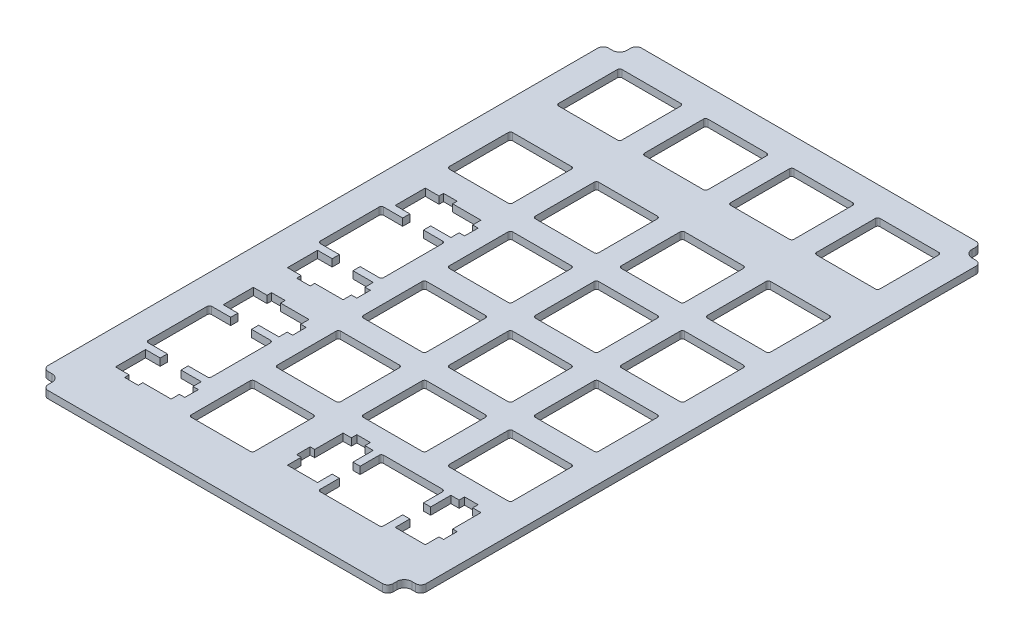
SolidWorks part; units mm, degrees
ref_plane "前视基准面" through (0, 0, 0) normal (0, 0, 1) x (1, 0, 0)
ref_plane "上视基准面" through (0, 0, 0) normal (0, 1, 0) x (1, 0, 0)
ref_plane "右视基准面" through (0, 0, 0) normal (1, 0, 0) x (0, 0, -1)
sketch "草图1" plane through (0, 0, 0) normal (0, 1, 0) x (1, 0, 0)
  line L17 (-11.3508, 119.1658) -> (-10.5008, 119.1658)
  line L18 (-8.8508, 120.8158) -> (-8.8508, 121.6658)
  line L19 (50.8492, 119.1658) -> (49.9992, 119.1658)
  line L20 (48.3492, 120.8158) -> (48.3492, 121.6658)
  line L21 (47.1992, 122.8158) -> (-7.7008, 122.8158)
  line L22 (-8.8508, 121.6658) -> (-8.8508, 120.8158)
  line L23 (-10.5008, 119.1658) -> (-11.3508, 119.1658)
  line L24 (-12.5008, 118.0158) -> (-12.5008, -3.4717)
  line L25 (-11.3508, -4.6217) -> (-10.5008, -4.6217)
  line L26 (-8.8508, -6.2717) -> (-8.8508, -7.1217)
  line L27 (-7.7008, -8.2717) -> (47.1992, -8.2717)
  line L28 (48.3492, -7.1217) -> (48.3492, -6.2717)
  line L29 (49.9992, -4.6217) -> (50.8492, -4.6217)
  line L30 (51.9992, -3.4717) -> (51.9992, 97.2055)
  line L37 (-11.3508, -4.6217) -> (-10.5008, -4.6217)
  line L38 (-8.8508, -6.2717) -> (-8.8508, -7.1217)
  line L43 (68.9992, 119.1658) -> (69.8492, 119.1658)
  line L44 (67.3492, 121.6658) -> (67.3492, 120.8158)
  line L45 (66.1992, 122.8158) -> (-7.7008, 122.8158)
  line L46 (70.9992, -3.4717) -> (70.9992, 118.0158)
  line L49 (66.1992, -8.2717) -> (-7.7008, -8.2717)
  line L50 (-12.5008, 118.0158) -> (-12.5008, -3.4717)
  line L53 (69.8492, -4.6217) -> (68.9992, -4.6217)
  line L54 (67.3492, -6.2717) -> (67.3492, -7.1217)
  line L266 (50.9992, 117.4055) -> (51.9992, 117.4055)
  line L268 (51.9992, 117.4055) -> (51.9992, 118.0158)
  line L270 (51.9992, 97.2055) -> (50.9992, 97.2055)
  line L272 (50.9992, 97.2055) -> (50.9992, 117.4055)
  arc A9 (-11.3508, 119.1658) -> (-12.5008, 118.0158) centre (-11.3508, 118.0158) ccw
  arc A10 (-10.5008, 119.1658) -> (-8.8508, 120.8158) centre (-10.5008, 120.8158) ccw
  arc A11 (-7.7008, 122.8158) -> (-8.8508, 121.6658) centre (-7.7008, 121.6658) ccw
  arc A12 (70.9992, 118.0158) -> (69.8492, 119.1658) centre (69.8492, 118.0158) ccw
  arc A13 (67.3492, 120.8158) -> (68.9992, 119.1658) centre (68.9992, 120.8158) ccw
  arc A14 (51.9992, 118.0158) -> (50.8492, 119.1658) centre (50.8492, 118.0158) ccw
  arc A15 (48.3492, 120.8158) -> (49.9992, 119.1658) centre (49.9992, 120.8158) ccw
  arc A16 (48.3492, 121.6658) -> (47.1992, 122.8158) centre (47.1992, 121.6658) ccw
  arc A17 (-7.7008, 122.8158) -> (-8.8508, 121.6658) centre (-7.7008, 121.6658) ccw
  arc A18 (-10.5008, 119.1658) -> (-8.8508, 120.8158) centre (-10.5008, 120.8158) ccw
  arc A19 (-11.3508, 119.1658) -> (-12.5008, 118.0158) centre (-11.3508, 118.0158) ccw
  arc A20 (-12.5008, -3.4717) -> (-11.3508, -4.6217) centre (-11.3508, -3.4717) ccw
  arc A21 (-8.8508, -6.2717) -> (-10.5008, -4.6217) centre (-10.5008, -6.2717) ccw
  arc A22 (-8.8508, -7.1217) -> (-7.7008, -8.2717) centre (-7.7008, -7.1217) ccw
  arc A23 (47.1992, -8.2717) -> (48.3492, -7.1217) centre (47.1992, -7.1217) ccw
  arc A24 (49.9992, -4.6217) -> (48.3492, -6.2717) centre (49.9992, -6.2717) ccw
  arc A25 (50.8492, -4.6217) -> (51.9992, -3.4717) centre (50.8492, -3.4717) ccw
  arc A32 (-12.5008, -3.4717) -> (-11.3508, -4.6217) centre (-11.3508, -3.4717) ccw
  arc A33 (-8.8508, -6.2717) -> (-10.5008, -4.6217) centre (-10.5008, -6.2717) ccw
  arc A34 (-8.8508, -7.1217) -> (-7.7008, -8.2717) centre (-7.7008, -7.1217) ccw
  arc A38 (67.3492, 121.6658) -> (66.1992, 122.8158) centre (66.1992, 121.6658) ccw
  arc A45 (69.8492, -4.6217) -> (70.9992, -3.4717) centre (69.8492, -3.4717) ccw
  arc A46 (68.9992, -4.6217) -> (67.3492, -6.2717) centre (68.9992, -6.2717) ccw
  arc A47 (66.1992, -8.2717) -> (67.3492, -7.1217) centre (66.1992, -7.1217) ccw
  dimension "D1" = 0
extrude "凸台-拉伸1" add sketch "草图1" along normal blind 1.6
sketch "草图6" plane through (0, 0, 0) normal (0, -1, 0) x (1, 0, 0)
  line L0 (-20.4509, -109.5658) -> (75.1048, -109.5658) construction
  line L1 (-30.8327, -47.4158) -> (78.7033, -47.4158) construction
  line L2 (29.2492, 25.694) -> (29.2492, -129.0357) construction
  line L3 (51.2492, -2.4158) -> (64.2492, -2.4158)
  line L4 (64.7492, -2.9158) -> (64.7492, -15.9158)
  line L5 (64.2492, -16.4158) -> (51.2492, -16.4158)
  line L6 (50.7492, -2.9158) -> (50.7492, -15.9158)
  line L7 (-28.6594, -9.4158) -> (85.6489, -9.4158) construction
  line L10 (67.2492, -99.3158) -> (-8.7508, -99.3158) construction
  line L11 (-9.5008, -100.0658) -> (-9.5008, -105.0658) construction
  line L12 (67.9992, -95.0158) -> (67.9992, 0.1842) construction
  line L13 (67.2492, 0.9342) -> (-8.7508, 0.9342) construction
  line L14 (67.9992, -105.0658) -> (67.9992, -100.0658) construction
  line L15 (67.9992, -119.0658) -> (67.9992, -114.0658) construction
  line L16 (-8.7508, -119.8158) -> (67.2492, -119.8158) construction
  line L17 (-9.5008, -114.0658) -> (-9.5008, -119.0658) construction
  line L18 (-9.5008, 0.1842) -> (-9.5008, -95.0158) construction
  line L19 (-8.7508, -95.7658) -> (67.2492, -95.7658) construction
  arc A0 (50.7492, -15.9158) -> (51.2492, -16.4158) centre (51.2492, -15.9158) ccw
  arc A1 (64.2492, -16.4158) -> (64.7492, -15.9158) centre (64.2492, -15.9158) ccw
  arc A2 (51.2492, -2.4158) -> (50.7492, -2.9158) centre (51.2492, -2.9158) ccw
  arc A3 (64.2492, -2.4158) -> (64.7492, -2.9158) centre (64.2492, -2.9158) cw
  dimension "D2" = 0.5
  dimension "D1" = 14
  dimension "D3" = 21.5
  dimension "D4" = 31
extrude "切除-拉伸3" cut sketch "草图6" against normal up to next
pattern_linear "阵列(线性)1" count 5 spacing 19 along (0, 0, -1) count 4 spacing 19 along (-1, 0, 0) skipping (0, 3), (1, 3), (2, 3), (3, 3) of "切除-拉伸3"
pattern_linear "阵列(线性)2" count 2 spacing 100.15 along (0, 0, -1) count 4 spacing 19 along (-1, 0, 0) skipping (0, 1), (0, 2), (0, 3) of "切除-拉伸3"
sketch "草图3" plane through (0, 1.6, 0) normal (0, 1, 0) x (1, 0, 0)
  line L0 (-24.3873, 18.9158) -> (58.3219, 18.9158) construction
  line L1 (0.7492, -13.1729) -> (0.7492, 58.2769) construction
  line L2 (-6.2508, 12.4158) -> (-6.2508, 25.4158)
  line L3 (7.7492, 25.4158) -> (7.7492, 12.4158)
  line L4 (-5.7508, 25.9158) -> (-1.5508, 25.9158)
  line L9 (-6.2508, 25.9158) -> (7.7492, 11.9158) construction
  line L10 (-6.2508, 11.9158) -> (7.7492, 25.9158) construction
  line L11 (-1.5508, 25.9158) -> (-1.5508, 27.4958)
  line L12 (-4.7808, 27.4958) -> (-1.5508, 27.4958)
  line L13 (-4.7808, 27.4958) -> (-4.7808, 34.1458)
  line L14 (-4.7808, 34.1458) -> (-1.7508, 34.1458)
  line L15 (-1.7508, 34.1458) -> (-1.7508, 35.1458)
  line L16 (-1.7508, 35.1458) -> (1.2492, 35.1458)
  line L17 (1.2492, 35.1458) -> (1.2492, 34.1458)
  line L18 (1.2492, 34.1458) -> (7.5192, 34.1458)
  line L19 (7.5192, 34.1458) -> (7.5192, 32.3208)
  line L20 (7.5192, 32.3208) -> (8.7192, 32.3208)
  line L21 (8.7192, 32.3208) -> (8.7192, 29.3208)
  line L22 (8.7192, 29.3208) -> (7.5192, 29.3208)
  line L23 (7.5192, 29.3208) -> (7.5192, 27.4958)
  line L24 (7.5192, 27.4958) -> (3.0492, 27.4958)
  line L25 (3.0492, 27.4958) -> (3.0492, 25.9158)
  line L26 (3.0492, 25.9158) -> (7.2492, 25.9158)
  line L27 (3.0492, 11.9158) -> (7.2492, 11.9158)
  line L28 (3.0492, 10.3358) -> (3.0492, 11.9158)
  line L29 (7.5192, 10.3358) -> (3.0492, 10.3358)
  line L30 (7.5192, 8.5108) -> (7.5192, 10.3358)
  line L31 (8.7192, 8.5108) -> (7.5192, 8.5108)
  line L32 (8.7192, 5.5108) -> (8.7192, 8.5108)
  line L33 (7.5192, 5.5108) -> (8.7192, 5.5108)
  line L34 (7.5192, 3.6858) -> (7.5192, 5.5108)
  line L35 (1.2492, 3.6858) -> (7.5192, 3.6858)
  line L36 (1.2492, 2.6858) -> (1.2492, 3.6858)
  line L37 (-1.7508, 2.6858) -> (1.2492, 2.6858)
  line L38 (-1.7508, 3.6858) -> (-1.7508, 2.6858)
  line L39 (-4.7808, 3.6858) -> (-1.7508, 3.6858)
  line L40 (-4.7808, 10.3358) -> (-4.7808, 3.6858)
  line L41 (-4.7808, 10.3358) -> (-1.5508, 10.3358)
  line L42 (-1.5508, 11.9158) -> (-1.5508, 10.3358)
  line L43 (-5.7508, 11.9158) -> (-1.5508, 11.9158)
  line L46 (-6.2508, 50.4158) -> (-6.2508, 63.4158)
  line L47 (7.7492, 63.4158) -> (7.7492, 50.4158)
  line L48 (-5.7508, 63.9158) -> (-1.5508, 63.9158)
  line L49 (-1.5508, 63.9158) -> (-1.5508, 65.4958)
  line L50 (-4.7808, 65.4958) -> (-1.5508, 65.4958)
  line L51 (-4.7808, 65.4958) -> (-4.7808, 72.1458)
  line L52 (-4.7808, 72.1458) -> (-1.7508, 72.1458)
  line L53 (-1.7508, 72.1458) -> (-1.7508, 73.1458)
  line L54 (-1.7508, 73.1458) -> (1.2492, 73.1458)
  line L55 (1.2492, 73.1458) -> (1.2492, 72.1458)
  line L56 (1.2492, 72.1458) -> (7.5192, 72.1458)
  line L57 (7.5192, 72.1458) -> (7.5192, 70.3208)
  line L58 (7.5192, 70.3208) -> (8.7192, 70.3208)
  line L59 (8.7192, 70.3208) -> (8.7192, 67.3208)
  line L60 (8.7192, 67.3208) -> (7.5192, 67.3208)
  line L61 (7.5192, 67.3208) -> (7.5192, 65.4958)
  line L62 (7.5192, 65.4958) -> (3.0492, 65.4958)
  line L63 (3.0492, 65.4958) -> (3.0492, 63.9158)
  line L64 (3.0492, 63.9158) -> (7.2492, 63.9158)
  line L65 (3.0492, 49.9158) -> (7.2492, 49.9158)
  line L66 (3.0492, 48.3358) -> (3.0492, 49.9158)
  line L67 (7.5192, 48.3358) -> (3.0492, 48.3358)
  line L68 (7.5192, 46.5108) -> (7.5192, 48.3358)
  line L69 (8.7192, 46.5108) -> (7.5192, 46.5108)
  line L70 (8.7192, 43.5108) -> (8.7192, 46.5108)
  line L71 (7.5192, 43.5108) -> (8.7192, 43.5108)
  line L72 (7.5192, 41.6858) -> (7.5192, 43.5108)
  line L73 (1.2492, 41.6858) -> (7.5192, 41.6858)
  line L74 (1.2492, 40.6858) -> (1.2492, 41.6858)
  line L75 (-1.7508, 40.6858) -> (1.2492, 40.6858)
  line L76 (-1.7508, 41.6858) -> (-1.7508, 40.6858)
  line L77 (-4.7808, 41.6858) -> (-1.7508, 41.6858)
  line L78 (-4.7808, 48.3358) -> (-4.7808, 41.6858)
  line L79 (-4.7808, 48.3358) -> (-1.5508, 48.3358)
  line L80 (-1.5508, 49.9158) -> (-1.5508, 48.3358)
  line L81 (-5.7508, 49.9158) -> (-1.5508, 49.9158)
  line L82 (-6.2508, 63.9158) -> (7.7492, 49.9158) construction
  line L83 (-6.2508, 49.9158) -> (7.7492, 63.9158) construction
  line L84 (32.2492, 16.4158) -> (45.2492, 16.4158) construction
  arc A0 (-6.2508, 25.4158) -> (-5.7508, 25.9158) centre (-5.7508, 25.4158) cw
  arc A1 (7.2492, 25.9158) -> (7.7492, 25.4158) centre (7.2492, 25.4158) cw
  arc A2 (7.2492, 11.9158) -> (7.7492, 12.4158) centre (7.2492, 12.4158) ccw
  arc A3 (-6.2508, 12.4158) -> (-5.7508, 11.9158) centre (-5.7508, 12.4158) ccw
  arc A4 (-6.2508, 63.4158) -> (-5.7508, 63.9158) centre (-5.7508, 63.4158) cw
  arc A5 (7.2492, 63.9158) -> (7.7492, 63.4158) centre (7.2492, 63.4158) cw
  arc A6 (7.2492, 49.9158) -> (7.7492, 50.4158) centre (7.2492, 50.4158) ccw
  arc A7 (-6.2508, 50.4158) -> (-5.7508, 49.9158) centre (-5.7508, 50.4158) ccw
  point P4 (0.7492, 18.9158)
  point P5 (0.7492, 18.9158)
  point P17 (-3.6508, 25.9158)
  point P64 (0.7492, 56.9158)
  point P65 (0.7492, 56.9158)
  dimension "D1" = 14
  dimension "D2" = 4.2
  dimension "D3" = 1.58
  dimension "D4" = 3.23
  dimension "D5" = 6.65
  dimension "D6" = 3.03
  dimension "D7" = 3
  dimension "D8" = 1
  dimension "D9" = 6.27
  dimension "D10" = 3
  dimension "D11" = 1.2
  dimension "D12" = 0.5
  dimension "D13" = 13
  dimension "D14" = 45
  dimension "D15" = 4.47
  dimension "D16" = 2
  dimension "D17" = 2.5
  dimension "D18" = 38
extrude "切除-拉伸2" cut sketch "草图3" against normal up to surface (1.6 mm away) up to face at (57.7492, 0, -109.5658)
sketch "草图7" plane through (0, 1.6, 0) normal (0, 1, 0) x (1, 0, 0)
  line L1 (30.8591, 16.9848) -> (66.3802, 16.9848)
  line L2 (30.8591, 16.9848) -> (30.8591, 1.1193)
  line L3 (30.8591, 1.1193) -> (66.3802, 1.1193)
  line L4 (66.3802, 16.9848) -> (66.3802, 1.1193)
extrude "凸台-拉伸2" add sketch "草图7" against normal up to surface (1.6 mm away) up to face at (2.1472, 0, -18.9158)
sketch "草图8" plane through (0, 1.6, 0) normal (0, 1, 0) x (1, 0, 0)
  line L0 (26.7492, 9.4158) -> (76.4498, 9.4158) construction
  line L1 (26.7492, 15.9158) -> (26.7492, 2.9158) construction
  line L2 (48.2492, 23.7044) -> (48.2492, -8.9571) construction
  line L3 (48.2492, 2.4158) -> (48.2492, 16.4158) construction
  line L4 (48.2492, 9.4158) -> (41.7492, 9.4158) construction
  line L72 (58.6542, 16.1858) -> (56.8292, 16.1858)
  line L73 (58.6542, 17.3858) -> (58.6542, 16.1858)
  line L74 (61.6542, 17.3858) -> (58.6542, 17.3858)
  line L75 (61.6542, 16.1858) -> (61.6542, 17.3858)
  line L76 (63.4792, 16.1858) -> (61.6542, 16.1858)
  line L77 (63.4792, 9.9158) -> (63.4792, 16.1858)
  line L78 (64.4792, 9.9158) -> (63.4792, 9.9158)
  line L79 (64.4792, 6.9158) -> (64.4792, 9.9158)
  line L80 (63.4792, 6.9158) -> (64.4792, 6.9158)
  line L81 (63.4792, 3.8858) -> (63.4792, 6.9158)
  line L82 (56.8292, 3.8858) -> (63.4792, 3.8858)
  line L83 (56.8292, 7.1158) -> (56.8292, 3.8858)
  line L84 (55.2492, 7.1158) -> (56.8292, 7.1158)
  line L85 (55.2492, 2.9158) -> (55.2492, 7.1158)
  line L86 (41.7492, 2.4158) -> (54.7492, 2.4158)
  line L87 (41.2492, 7.1158) -> (41.2492, 2.9158)
  line L88 (39.6692, 7.1158) -> (41.2492, 7.1158)
  line L89 (39.6692, 3.8858) -> (39.6692, 7.1158)
  line L90 (33.0192, 3.8858) -> (39.6692, 3.8858)
  line L91 (33.0192, 6.9158) -> (33.0192, 3.8858)
  line L92 (32.0192, 6.9158) -> (33.0192, 6.9158)
  line L93 (32.0192, 9.9158) -> (32.0192, 6.9158)
  line L94 (33.0192, 9.9158) -> (32.0192, 9.9158)
  line L95 (33.0192, 16.1858) -> (33.0192, 9.9158)
  line L96 (34.8442, 16.1858) -> (33.0192, 16.1858)
  line L97 (34.8442, 17.3858) -> (34.8442, 16.1858)
  line L98 (37.8442, 17.3858) -> (34.8442, 17.3858)
  line L99 (37.8442, 16.1858) -> (37.8442, 17.3858)
  line L100 (39.6692, 16.1858) -> (37.8442, 16.1858)
  line L101 (39.6692, 11.7158) -> (39.6692, 16.1858)
  line L102 (41.2492, 11.7158) -> (39.6692, 11.7158)
  line L103 (41.2492, 15.9158) -> (41.2492, 11.7158)
  line L104 (54.7492, 16.4158) -> (41.7492, 16.4158)
  line L105 (55.2492, 11.7158) -> (55.2492, 15.9158)
  line L106 (56.8292, 11.7158) -> (55.2492, 11.7158)
  line L107 (56.8292, 16.1858) -> (56.8292, 11.7158)
  arc A8 (54.7492, 2.4158) -> (55.2492, 2.9158) centre (54.7492, 2.9158) ccw
  arc A9 (41.2492, 2.9158) -> (41.7492, 2.4158) centre (41.7492, 2.9158) ccw
  arc A10 (41.7492, 16.4158) -> (41.2492, 15.9158) centre (41.7492, 15.9158) ccw
  arc A11 (55.2492, 15.9158) -> (54.7492, 16.4158) centre (54.7492, 15.9158) ccw
  point P22 (48.2492, 9.4158)
extrude "切除-拉伸4" cut sketch "草图8" against normal up to surface (1.6 mm away) up to face at (2.1472, 0, -18.9158)
